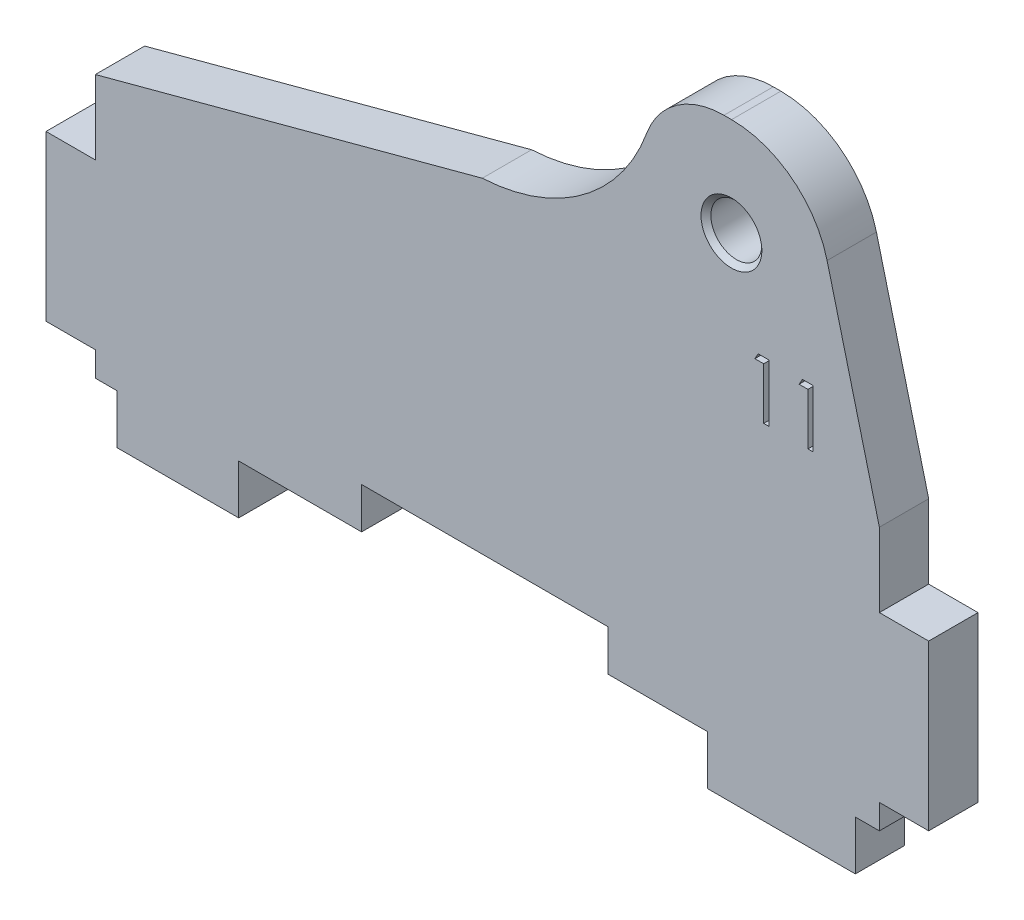
SolidWorks part; units mm, degrees
ref_plane "前视基准面" through (0, 0, 0) normal (0, 0, 1) x (1, 0, 0)
ref_plane "上视基准面" through (0, 0, 0) normal (0, 1, 0) x (1, 0, 0)
ref_plane "右视基准面" through (0, 0, 0) normal (1, 0, 0) x (0, 0, -1)
ref_plane "基准面4" through (0, 0, 0) normal (0, 0, -1) x (-1, 0, 0)
sketch "草图1" plane through (0, 0, 0) normal (0, 0, -1) x (-1, 0, 0)
  line L0 (-47.5193, 26.9593) -> (-50.6992, 14.4996)
  line L1 (-50.6992, 14.4996) -> (-50.6992, 10.0003)
  line L2 (-50.6992, 10.0003) -> (-53.6992, 10.0003)
  line L3 (-53.6992, 10.0003) -> (-53.6992, 0)
  line L4 (-53.6992, 0) -> (-50.6992, 0)
  line L5 (-50.6992, 0) -> (-50.6992, -1.5007)
  line L6 (-50.6992, -1.5007) -> (-49.2382, -1.5007)
  line L7 (-49.2382, -1.5007) -> (-49.2382, -4.5007)
  line L8 (-49.2382, -4.5007) -> (-40.2392, -4.5007)
  line L9 (-40.2392, -4.5007) -> (-40.2392, -1.4993)
  line L10 (-40.2392, -1.4993) -> (-34.2002, -1.4993)
  line L11 (-34.2002, -1.4993) -> (-34.2002, 1.0005)
  line L12 (-34.2002, 1.0005) -> (-19.2003, 1.0005)
  line L13 (-19.2003, 1.0005) -> (-19.2003, -1.4993)
  line L14 (-19.2003, -1.4993) -> (-11.7217, -1.4993)
  line L15 (-11.7217, -1.4993) -> (-11.7217, -4.5007)
  line L16 (-11.7217, -4.5007) -> (-4.3215, -4.5007)
  line L17 (-4.3215, -4.5007) -> (-4.3215, -1.5007)
  line L18 (-4.3215, -1.5007) -> (-3, -1.5007)
  line L19 (-3, -1.5007) -> (-3, 0)
  line L20 (-3, 0) -> (0, 0)
  line L21 (0, 0) -> (0, 10.0003)
  line L22 (0, 10.0003) -> (-3, 10.0003)
  line L23 (-3, 10.0003) -> (-3, 14.4996)
  line L24 (-3, 14.4996) -> (-26.5435, 20.8078)
  line L25 (-41.2462, 31.4756) -> (-41.7057, 31.4756)
  arc A0 (-41.7057, 31.4756) -> (-47.5193, 26.9593) centre (-41.7057, 25.4756) ccw
  arc A1 (-26.5435, 20.8078) -> (-36.5489, 28.1889) centre (-25.98, 32.0437) cw
  arc A2 (-36.5489, 28.1889) -> (-41.2462, 31.4756) centre (-41.2462, 26.4756) ccw
  circle A3 centre (-41.6992, 25.4997) radius 1.55
extrude "凸台-拉伸1" add sketch "草图1" against normal blind 3
sketch "草图2" plane through (0, 0, 3) normal (0, 0, 1) x (1, 0, 0)
  text T0 "11"
extrude "切除-拉伸1" cut sketch "草图2" against normal blind 1
chamfer "倒角1" distance 0.3 angle 45 2 edges at (43.2492, 25.4997, 0) (43.2492, 25.4997, 3)
